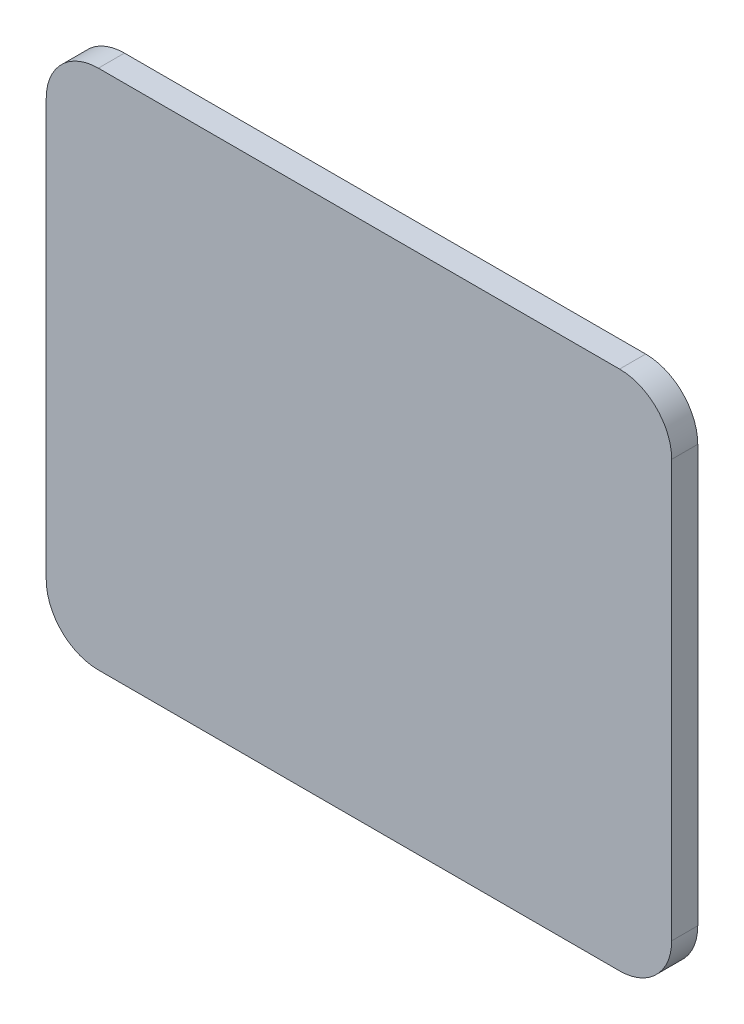
SolidWorks part; units mm, degrees
ref_plane "Płaszczyzna przednia" through (0, 0, 0) normal (0, 0, 1) x (1, 0, 0)
ref_plane "Płaszczyzna górna" through (0, 0, 0) normal (0, 1, 0) x (1, 0, 0)
ref_plane "Płaszczyzna prawa" through (0, 0, 0) normal (1, 0, 0) x (0, 0, -1)
sketch "Szkic1" plane through (0, 0, 0) normal (0, 0, 1) x (1, 0, 0)
  line L1 (-60, -50) -> (60, -50)
  line L2 (-60, -50) -> (-60, 50)
  line L3 (-60, 50) -> (60, 50)
  line L4 (60, -50) -> (60, 50)
  line L5 (-60, -50) -> (60, 50) construction
  line L6 (-60, 50) -> (60, -50) construction
  point P0 (0, 0)
  dimension "D1" = 100
  dimension "D2" = 120
extrude "Dodanie-wyciągnięcie1" add sketch "Szkic1" along normal blind 5 contours L3 L4 L1 L2
fillet "Zaokrąglenie1" radius 10 4 edges at (-60, 50, 2.5) (-60, -50, 2.5) (60, -50, 2.5) (60, 50, 2.5)
